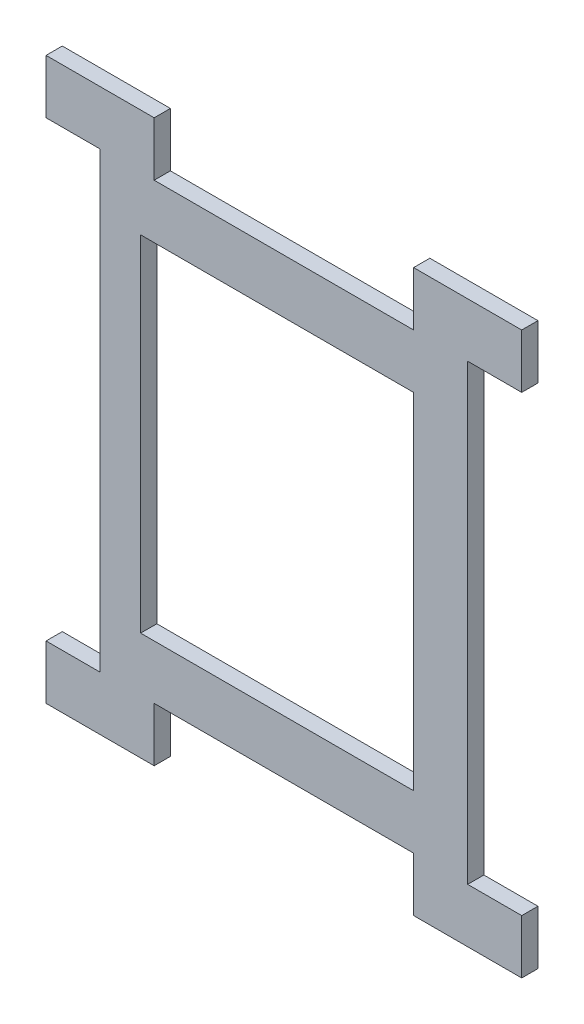
SolidWorks part; units mm, degrees
ref_plane "Спереди" through (0, 0, 0) normal (0, 0, 1) x (1, 0, 0)
ref_plane "Сверху" through (0, 0, 0) normal (0, 1, 0) x (1, 0, 0)
ref_plane "Справа" through (0, 0, 0) normal (1, 0, 0) x (0, 0, -1)
sketch "Эскиз1" plane through (0, 0, 0) normal (0, 0, 1) x (1, 0, 0)
  line L0 (-37.1907, 32.8973) -> (-37.1907, 22.8973)
  line L1 (-37.1907, 22.8973) -> (-27.1907, 22.8973)
  line L2 (-27.1907, 22.8973) -> (-27.1907, -60.9121)
  line L3 (-27.1907, -60.9121) -> (-37.1907, -60.9121)
  line L4 (-37.1907, -60.9121) -> (-37.1907, -70.9121)
  line L5 (-37.1907, -70.9121) -> (-17.1907, -70.9121)
  line L6 (-17.1907, -70.9121) -> (-17.1907, -60.9121)
  line L7 (-17.1907, -60.9121) -> (30.7988, -60.9121)
  line L8 (30.7988, -60.9121) -> (30.7988, -70.9121)
  line L9 (30.7988, -70.9121) -> (50.7988, -70.9121)
  line L10 (50.7988, -70.9121) -> (50.7988, -60.9121)
  line L11 (50.7988, -60.9121) -> (40.7988, -60.9121)
  line L12 (40.7988, -60.9121) -> (40.7988, 22.8973)
  line L13 (40.7988, 22.8973) -> (50.7988, 22.8973)
  line L14 (50.7988, 22.8973) -> (50.7988, 32.8973)
  line L15 (50.7988, 32.8973) -> (30.7988, 32.8973)
  line L16 (30.7988, 32.8973) -> (30.7988, 22.8973)
  line L17 (30.7988, 22.8973) -> (-17.1907, 22.8973)
  line L18 (-17.1907, 22.8973) -> (-17.1907, 32.8973)
  line L19 (-17.1907, 32.8973) -> (-37.1907, 32.8973)
  line L21 (-19.6971, 12.8973) -> (30.7988, 12.8973)
  line L22 (-19.6971, 12.8973) -> (-19.6971, -50.9121)
  line L23 (-19.6971, -50.9121) -> (30.7988, -50.9121)
  line L24 (30.7988, 12.8973) -> (30.7988, -50.9121)
  line L25 (-19.6971, 12.8973) -> (30.7988, -50.9121) construction
  line L26 (-19.6971, -50.9121) -> (30.7988, 12.8973) construction
  point P2 (5.5509, -19.0074)
  dimension "D1" = 10
  dimension "D2" = 10
  dimension "D3" = 10
  dimension "D4" = 10
  dimension "D5" = 10
  dimension "D6" = 10
  dimension "D7" = 10
extrude "Бобышка-Вытянуть1" add sketch "Эскиз1" along normal blind 3
